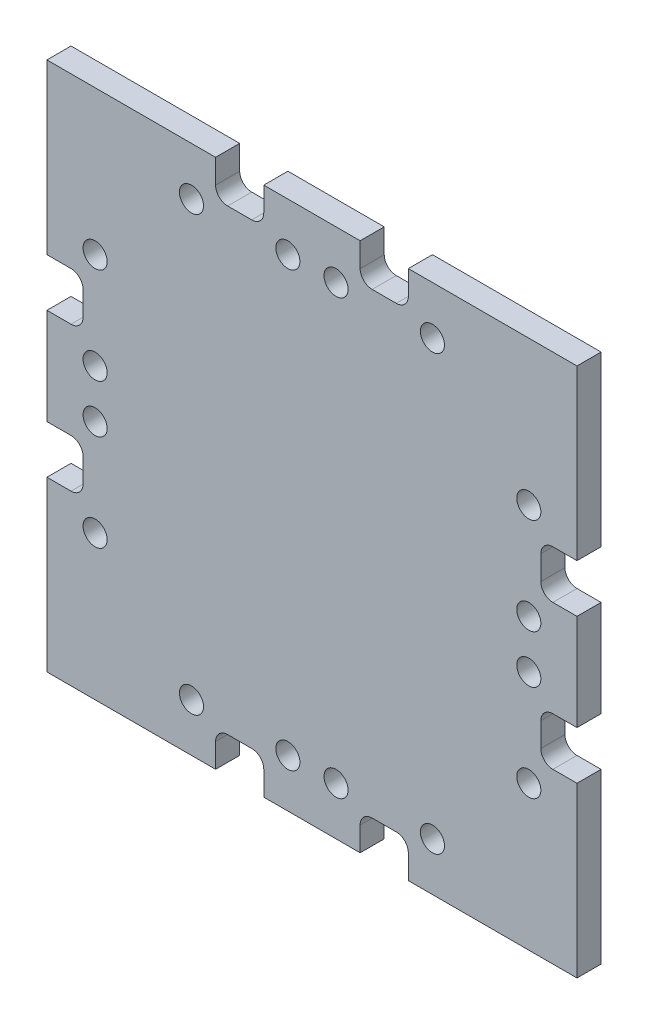
SolidWorks part; units mm, degrees
material "自訂玻璃纖維"
ref_plane "前基準面" through (0, 0, 0) normal (0, 0, 1) x (1, 0, 0)
ref_plane "上基準面" through (0, 0, 0) normal (0, 1, 0) x (1, 0, 0)
ref_plane "右基準面" through (0, 0, 0) normal (1, 0, 0) x (0, 0, -1)
sketch "草圖1" plane through (0, 0, 0) normal (0, 0, 1) x (1, 0, 0)
  line L0 (-19.2462, 5.7936) -> (-17.2462, 5.7936)
  line L1 (-19.2462, 13.7936) -> (24.7538, 13.7936)
  line L2 (-19.2462, 13.7936) -> (-19.2462, 5.7936)
  line L3 (-19.2462, -18.2064) -> (24.7538, -18.2064)
  line L4 (24.7538, 13.7936) -> (24.7538, 5.7936)
  line L5 (-19.2462, 1.7936) -> (-19.2462, -6.2064)
  line L6 (-17.2462, 1.7936) -> (-19.2462, 1.7936)
  line L7 (-16.2462, 4.7936) -> (-16.2462, 2.7936)
  line L8 (-19.2462, -10.2064) -> (-19.2462, -18.2064)
  line L9 (-16.2462, -9.2064) -> (-16.2462, -7.2064)
  line L10 (-17.2462, -6.2064) -> (-19.2462, -6.2064)
  line L11 (-19.2462, -10.2064) -> (-17.2462, -10.2064)
  line L12 (24.7538, 1.7936) -> (24.7538, -6.2064)
  line L13 (24.7538, -10.2064) -> (22.7538, -10.2064)
  line L14 (22.7538, -6.2064) -> (24.7538, -6.2064)
  line L15 (21.7538, -9.2064) -> (21.7538, -7.2064)
  line L16 (21.7538, 4.7936) -> (21.7538, 2.7936)
  line L17 (22.7538, 1.7936) -> (24.7538, 1.7936)
  line L18 (24.7538, 5.7936) -> (22.7538, 5.7936)
  line L19 (24.7538, -10.2064) -> (24.7538, -18.2064)
  circle A0 centre (-15.2462, 7.7936) radius 1
  circle A1 centre (-15.2462, -0.2064) radius 1
  circle A2 centre (20.7538, -12.2064) radius 1
  circle A3 centre (20.7538, 7.7936) radius 1
  circle A4 centre (-15.2462, -4.2064) radius 1
  circle A5 centre (-15.2462, -12.2064) radius 1
  circle A6 centre (20.7538, -0.2064) radius 1
  circle A7 centre (20.7538, -4.2064) radius 1
  arc A8 (-17.2462, 5.7936) -> (-16.2462, 4.7936) centre (-17.2462, 4.7936) cw
  arc A9 (-16.2462, 2.7936) -> (-17.2462, 1.7936) centre (-17.2462, 2.7936) cw
  arc A10 (-16.2462, -7.2064) -> (-17.2462, -6.2064) centre (-17.2462, -7.2064) ccw
  arc A11 (-17.2462, -10.2064) -> (-16.2462, -9.2064) centre (-17.2462, -9.2064) ccw
  arc A12 (22.7538, -10.2064) -> (21.7538, -9.2064) centre (22.7538, -9.2064) cw
  arc A13 (21.7538, -7.2064) -> (22.7538, -6.2064) centre (22.7538, -7.2064) cw
  arc A14 (21.7538, 2.7936) -> (22.7538, 1.7936) centre (22.7538, 2.7936) ccw
  arc A15 (22.7538, 5.7936) -> (21.7538, 4.7936) centre (22.7538, 4.7936) ccw
  dimension "D3" = 2
  dimension "D4" = 8
  dimension "D5" = 4
  dimension "D7" = 4
  dimension "D8" = 4
  dimension "D9" = 4
  dimension "D10" = 4
  dimension "D11" = 4
  dimension "D12" = 8
  dimension "D13" = 4
  dimension "D15" = 2
  dimension "D1" = 44
  dimension "D2" = 32
  dimension "D14" = 2
extrude "填料-伸長4" add sketch "草圖1" along normal blind 2
fillet "圓角1" radius 1 4 edges at (-19.2462, 13.7936, 1) (24.7538, 13.7936, 1) (24.7538, -18.2064, 1) (-19.2462, -18.2064, 1)
sketch "草圖4" plane through (0, 0, 2) normal (0, 0, 1) x (1, 0, 0)
  line L0 (-19.2462, -21.2064) -> (-19.2462, -17.2064)
  line L1 (-19.2462, 12.7936) -> (24.7538, 12.7936)
  line L2 (-19.2462, 12.7936) -> (-19.2462, 16.7936)
  line L3 (-18.2462, 17.7936) -> (23.7538, 17.7936)
  line L4 (24.7538, 12.7936) -> (24.7538, 16.7936)
  line L5 (-19.2462, -17.2064) -> (24.7538, -17.2064)
  line L7 (-18.2462, -22.2064) -> (23.7538, -22.2064)
  line L8 (24.7538, -17.2064) -> (24.7538, -21.2064)
  arc A0 (-19.2462, -21.2064) -> (-18.2462, -22.2064) centre (-18.2462, -21.2064) ccw
  arc A1 (23.7538, -22.2064) -> (24.7538, -21.2064) centre (23.7538, -21.2064) ccw
  arc A2 (23.7538, 17.7936) -> (24.7538, 16.7936) centre (23.7538, 16.7936) cw
  arc A3 (-19.2462, 16.7936) -> (-18.2462, 17.7936) centre (-18.2462, 16.7936) cw
  point P14 (24.7538, -22.2064)
  point P17 (24.7538, 17.7936)
  dimension "D3" = 1
  dimension "D1" = 5
  dimension "D2" = 5
extrude "填料-伸長5" add sketch "草圖4" against normal blind 2
sketch "草圖5" plane through (0, 0, 2) normal (0, 0, 1) x (1, 0, 0)
  line L0 (23.7538, 17.7936) -> (-18.2462, 17.7936) construction
  line L1 (-5.2462, 19.7936) -> (-1.2462, 19.7936)
  line L2 (-5.2462, 19.7936) -> (-5.2462, 17.7936)
  line L4 (-1.2462, 17.7936) -> (-1.2462, 19.7936)
  line L5 (-4.2462, 16.7936) -> (-2.2462, 16.7936)
  line L6 (9.7538, 16.7936) -> (7.7538, 16.7936)
  line L7 (6.7538, 17.7936) -> (6.7538, 19.7936)
  line L8 (10.7538, 19.7936) -> (10.7538, 17.7936)
  line L9 (10.7538, 19.7936) -> (6.7538, 19.7936)
  line L11 (10.7538, -24.2064) -> (6.7538, -24.2064)
  line L12 (10.7538, -24.2064) -> (10.7538, -22.2064)
  line L13 (6.7538, -22.2064) -> (6.7538, -24.2064)
  line L14 (9.7538, -21.2064) -> (7.7538, -21.2064)
  line L15 (-4.2462, -21.2064) -> (-2.2462, -21.2064)
  line L16 (-1.2462, -22.2064) -> (-1.2462, -24.2064)
  line L17 (-5.2462, -24.2064) -> (-5.2462, -22.2064)
  line L18 (-5.2462, -24.2064) -> (-1.2462, -24.2064)
  circle A0 centre (12.7538, 15.7936) radius 1
  circle A1 centre (0.7538, 15.7936) radius 1
  circle A2 centre (0.7538, -20.2064) radius 1
  circle A3 centre (-7.2462, -20.2064) radius 1
  circle A4 centre (4.7538, -20.2064) radius 1
  circle A5 centre (12.7538, -20.2064) radius 1
  circle A6 centre (-7.2462, 15.7936) radius 1
  circle A7 centre (4.7538, 15.7936) radius 1
  arc A8 (-5.2462, 17.7936) -> (-4.2462, 16.7936) centre (-4.2462, 17.7936) ccw
  arc A9 (-2.2462, 16.7936) -> (-1.2462, 17.7936) centre (-2.2462, 17.7936) ccw
  arc A10 (7.7538, 16.7936) -> (6.7538, 17.7936) centre (7.7538, 17.7936) cw
  arc A11 (10.7538, 17.7936) -> (9.7538, 16.7936) centre (9.7538, 17.7936) cw
  arc A12 (10.7538, -22.2064) -> (9.7538, -21.2064) centre (9.7538, -22.2064) ccw
  arc A13 (7.7538, -21.2064) -> (6.7538, -22.2064) centre (7.7538, -22.2064) ccw
  arc A14 (-2.2462, -21.2064) -> (-1.2462, -22.2064) centre (-2.2462, -22.2064) cw
  arc A15 (-5.2462, -22.2064) -> (-4.2462, -21.2064) centre (-4.2462, -22.2064) cw
  point P0 (2.7538, 15.7936)
  point P7 (2.7538, -20.2064)
  dimension "D1" = 2
  dimension "D2" = 2
  dimension "D3" = 2
  dimension "D4" = 2
  dimension "D5" = 2
  dimension "D6" = 8
  dimension "D7" = 2
  dimension "D8" = 2
  dimension "D9" = 8
  dimension "D13" = 2
extrude "除料-伸長3" cut sketch "草圖5" against normal blind 2
sketch "草圖6" plane through (0, 0, 2) normal (0, 0, 1) x (1, 0, 0)
  line L0 (-19.2462, -23.2064) -> (-19.2462, -21.2064)
  line L1 (-19.2462, 16.7936) -> (-5.2462, 16.7936)
  line L2 (-19.2462, 16.7936) -> (-19.2462, 18.7936)
  line L3 (-18.2462, 19.7936) -> (-5.2462, 19.7936)
  line L4 (24.7538, 16.7936) -> (24.7538, 18.7936)
  line L5 (-19.2462, -21.2064) -> (-5.2462, -21.2064)
  line L6 (-5.2462, 17.7936) -> (-5.2462, 16.7936)
  line L7 (-18.2462, -24.2064) -> (-5.2462, -24.2064)
  line L8 (24.7538, -21.2064) -> (24.7538, -23.2064)
  line L9 (-1.2462, 17.7936) -> (-1.2462, 16.7936)
  line L10 (-1.2462, 16.7936) -> (6.7538, 16.7936)
  line L11 (-5.2462, 17.7936) -> (-5.2462, 19.7936)
  line L12 (-1.2462, 17.7936) -> (-1.2462, 19.7936)
  line L13 (-1.2462, 19.7936) -> (6.7538, 19.7936)
  line L14 (6.7538, 19.7936) -> (6.7538, 16.7936)
  line L15 (10.7538, 19.7936) -> (10.7538, 16.7936)
  line L16 (10.7538, 16.7936) -> (24.7538, 16.7936)
  line L17 (10.7538, 19.7936) -> (23.7538, 19.7936)
  line L18 (-1.2462, -24.2064) -> (6.7538, -24.2064)
  line L19 (10.7538, -24.2064) -> (23.7538, -24.2064)
  line L20 (-5.2462, -24.2064) -> (-5.2462, -21.2064)
  line L21 (10.7538, -21.2064) -> (24.7538, -21.2064)
  line L22 (-1.2462, -24.2064) -> (-1.2462, -21.2064)
  line L23 (-19.2462, -23.2064) -> (-19.2462, -24.2064)
  line L24 (6.7538, -24.2064) -> (6.7538, -21.2064)
  line L25 (-19.2462, -24.2064) -> (-18.2462, -24.2064)
  line L26 (10.7538, -24.2064) -> (10.7538, -21.2064)
  line L27 (-1.2462, -21.2064) -> (6.7538, -21.2064)
  line L28 (23.7538, -24.2064) -> (24.7538, -24.2064)
  line L29 (24.7538, -24.2064) -> (24.7538, -23.2064)
  line L30 (23.7538, 19.7936) -> (24.7538, 19.7936)
  line L31 (24.7538, 19.7936) -> (24.7538, 18.7936)
  line L32 (-18.2462, 19.7936) -> (-19.2462, 19.7936)
  line L33 (-19.2462, 19.7936) -> (-19.2462, 18.7936)
  arc A4 (-19.2462, -21.2064) -> (-18.2462, -22.2064) centre (-18.2462, -21.2064) ccw construction
  point P14 (24.7538, -24.2064)
  point P17 (24.7538, 19.7936)
  dimension "D1" = 3
  dimension "D2" = 3
extrude "填料-伸長6" add sketch "草圖6" against normal blind 2
